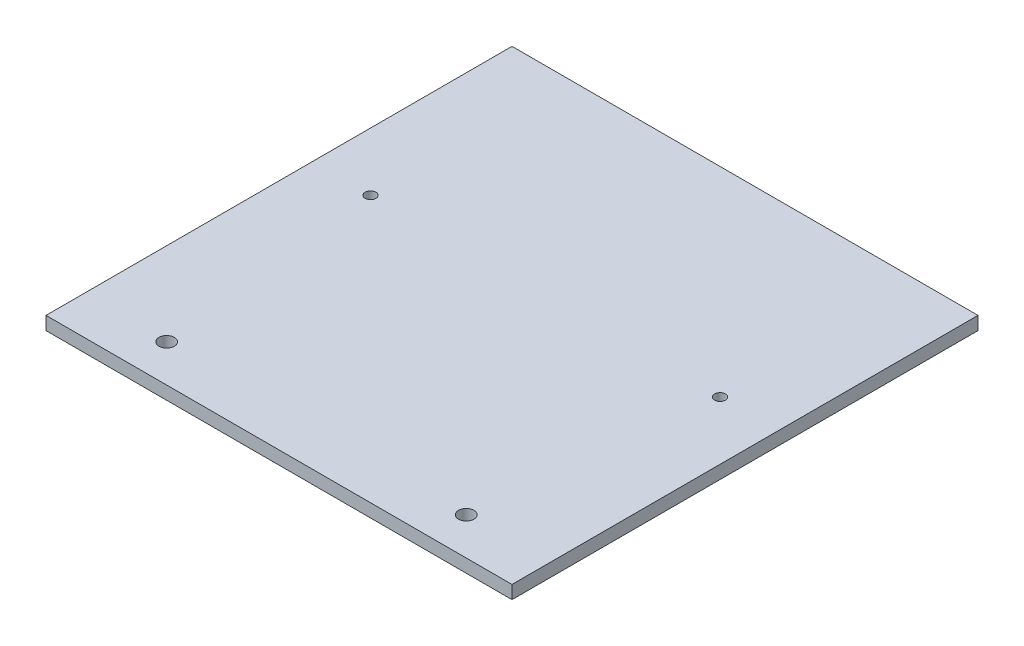
SolidWorks part; units mm, degrees
material "Pin"
ref_plane "Plan de face" through (0, 0, 0) normal (0, 0, 1) x (1, 0, 0)
ref_plane "Plan de dessus" through (0, 0, 0) normal (0, 1, 0) x (1, 0, 0)
ref_plane "Plan de droite" through (0, 0, 0) normal (1, 0, 0) x (0, 0, -1)
sketch "Esquisse1" plane through (0, 0, 0) normal (0, 1, 0) x (1, 0, 0)
  line L1 (-56, 56) -> (56, 56)
  line L2 (-56, 56) -> (-56, -56)
  line L3 (-56, -56) -> (56, -56)
  line L4 (56, 56) -> (56, -56)
  point P4 (0, 56)
  point P6 (-56, 0)
  dimension "D1" = 112
  dimension "D2" = 112
extrude "Boss.-Extru.1" add sketch "Esquisse1" along normal blind 3.175
hole_wizard "Dégagement M41" positions "Esquisse2" profile "Esquisse3" hole size "M4" standard "Ansi Metric"
sketch "Esquisse2" plane through (0, 3.175, 0) normal (0, 1, 0) x (1, 0, 0)
  line L0 (36, -47) -> (-36, -47) construction
  line L1 (-56, -56) -> (56, -56) construction
  point P0 (-36, -47)
  point P13 (36, -47)
  point P20 (0, -47)
  dimension "D1" = 72
  dimension "D2" = 9
sketch "Esquisse3" plane through (-36, 3.175, 47) normal (1, 0, 0) x (0, 0, 1)
  line L0 (0, 0) -> (0, 4.2866)
  line L1 (0, 4.2866) -> (1.85, 3.175)
  line L2 (1.85, 3.175) -> (1.85, 0)
  line L5 (1.85, 0) -> (0, 0)
  line L10 (0, 4.2866) -> (-1.85, 3.175) construction
  line L11 (0, -6.35) -> (0, 107.95) construction
  dimension "Diamètre du perçage" = 3.7
  dimension "Profondeur du perçage" = 3.175
  dimension "Angle de pointe" = 118
sketch "Esquisse4" plane through (0, 3.175, 0) normal (0, 1, 0) x (1, 0, 0)
  line L0 (42, 8) -> (-42, 8) construction
  point P2 (0, 8)
  dimension "D1" = 84
  dimension "D2" = 8
hole_wizard "Dégagement M32" positions "Esquisse7" profile "Esquisse6" hole size "M3" standard "Ansi Metric"
sketch "Esquisse7" plane through (0, 3.175, 0) normal (0, 1, 0) x (1, 0, 0)
  point P0 (42, 8)
  point P3 (-42, 8)
sketch "Esquisse6" plane through (42, 3.175, -8) normal (1, 0, 0) x (0, 0, 1)
  line L0 (0, 0) -> (0, 3.9561)
  line L1 (0, 3.9561) -> (1.3, 3.175)
  line L2 (1.3, 3.175) -> (1.3, 0)
  line L5 (1.3, 0) -> (0, 0)
  line L10 (0, 3.9561) -> (-1.3, 3.175) construction
  line L11 (0, -6.35) -> (0, 107.95) construction
  dimension "Diamètre du perçage" = 2.6
  dimension "Profondeur du perçage" = 3.175
  dimension "Angle de pointe" = 118
